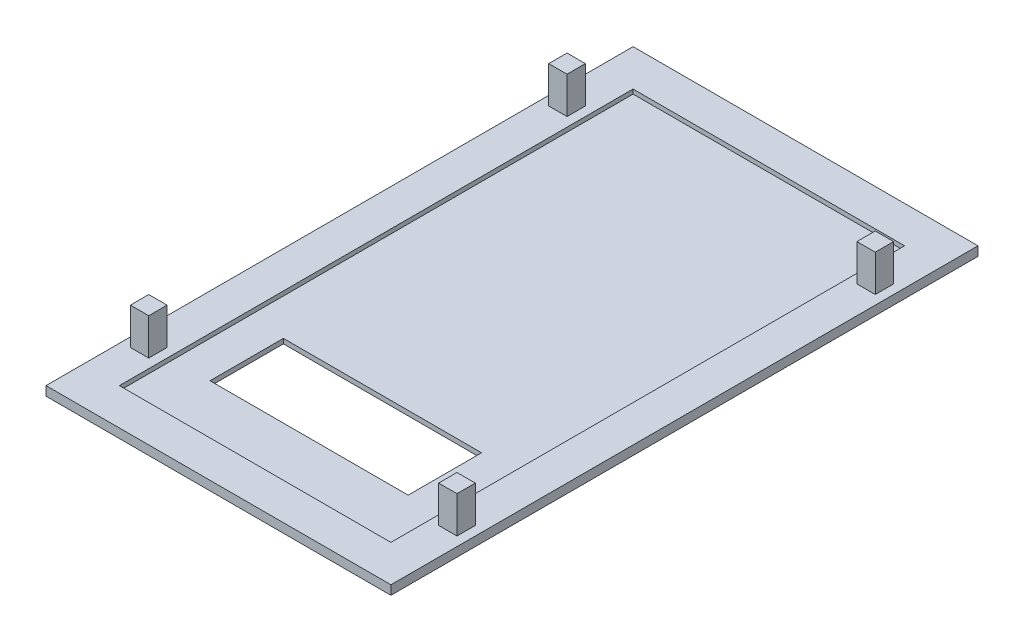
SolidWorks part; units mm, degrees
ref_plane "Front Plane" through (0, 0, 0) normal (0, 0, 1) x (1, 0, 0)
ref_plane "Top Plane" through (0, 0, 0) normal (0, 1, 0) x (1, 0, 0)
ref_plane "Right Plane" through (0, 0, 0) normal (1, 0, 0) x (0, 0, -1)
sketch "Sketch1" plane through (0, 0, 0) normal (0, 1, 0) x (1, 0, 0)
  line L1 (0, 0) -> (47, 0)
  line L2 (0, 0) -> (0, 80)
  line L3 (0, 80) -> (47, 80)
  line L4 (47, 0) -> (47, 80)
  dimension "D1" = 80
  dimension "D2" = 47
extrude "Boss-Extrude1" add sketch "Sketch1" along normal blind 1.25
sketch "Sketch2" plane through (0, 1.25, 0) normal (0, 1, 0) x (1, 0, 0)
  line L0 (47, 0) -> (47, 80) construction
  line L1 (43.25, 69.75) -> (45.75, 69.75)
  line L2 (43.25, 69.75) -> (43.25, 67.25)
  line L3 (43.25, 67.25) -> (45.75, 67.25)
  line L4 (45.75, 69.75) -> (45.75, 67.25)
  line L5 (47, 80) -> (0, 80) construction
  line L6 (0, 0) -> (47, 0) construction
  line L7 (45.75, 12.75) -> (43.25, 12.75)
  line L8 (45.75, 12.75) -> (45.75, 10.25)
  line L9 (45.75, 10.25) -> (43.25, 10.25)
  line L10 (43.25, 12.75) -> (43.25, 10.25)
  line L11 (0, 80) -> (0, 0) construction
  line L12 (1.25, 10.25) -> (3.75, 10.25)
  line L13 (1.25, 10.25) -> (1.25, 12.75)
  line L14 (1.25, 12.75) -> (3.75, 12.75)
  line L15 (3.75, 10.25) -> (3.75, 12.75)
  line L17 (1.25, 69.75) -> (3.75, 69.75)
  line L18 (1.25, 69.75) -> (1.25, 67.25)
  line L19 (1.25, 67.25) -> (3.75, 67.25)
  line L20 (3.75, 69.75) -> (3.75, 67.25)
  point P12 (44.5, 10.25)
  dimension "D1" = 2.5
  dimension "D2" = 2.5
  dimension "D3" = 1.25
  dimension "D4" = 10.25
  dimension "D5" = 2.5
  dimension "D6" = 2.5
  dimension "D7" = 1.25
  dimension "D8" = 10.25
  dimension "D9" = 2.5
  dimension "D10" = 2.5
  dimension "D11" = 1.25
  dimension "D12" = 10.25
  dimension "D13" = 2.5
  dimension "D14" = 2.5
  dimension "D15" = 1.25
  dimension "D16" = 10.25
extrude "Boss-Extrude2" add sketch "Sketch2" along normal blind 5
sketch "Sketch3" plane through (0, 1.25, 0) normal (0, 1, 0) x (1, 0, 0)
  line L0 (0, 0) -> (47, 0) construction
  line L1 (10, 22.35) -> (37, 22.35)
  line L2 (10, 22.35) -> (10, 12.35)
  line L3 (10, 12.35) -> (37, 12.35)
  line L4 (37, 22.35) -> (37, 12.35)
  line L5 (0, 80) -> (0, 0) construction
  line L6 (47, 0) -> (47, 80) construction
  dimension "D1" = 12.35
  dimension "D2" = 10
  dimension "D3" = 10
  dimension "D4" = 10
extrude "Cut-Extrude1" cut sketch "Sketch3" against normal blind 5
sketch "Sketch6" plane through (0, 1.25, 0) normal (0, 1, 0) x (1, 0, 0)
  line L0 (0, 80) -> (0, 0) construction
  line L1 (5, 75) -> (42, 75)
  line L2 (5, 75) -> (5, 5)
  line L3 (5, 5) -> (42, 5)
  line L4 (42, 75) -> (42, 5)
  line L5 (47, 80) -> (0, 80) construction
  line L6 (47, 0) -> (47, 80) construction
  line L7 (0, 0) -> (47, 0) construction
  dimension "D1" = 5
  dimension "D2" = 5
  dimension "D3" = 5
  dimension "D4" = 5
extrude "Cut-Extrude2" cut sketch "Sketch6" against normal blind 0.6
